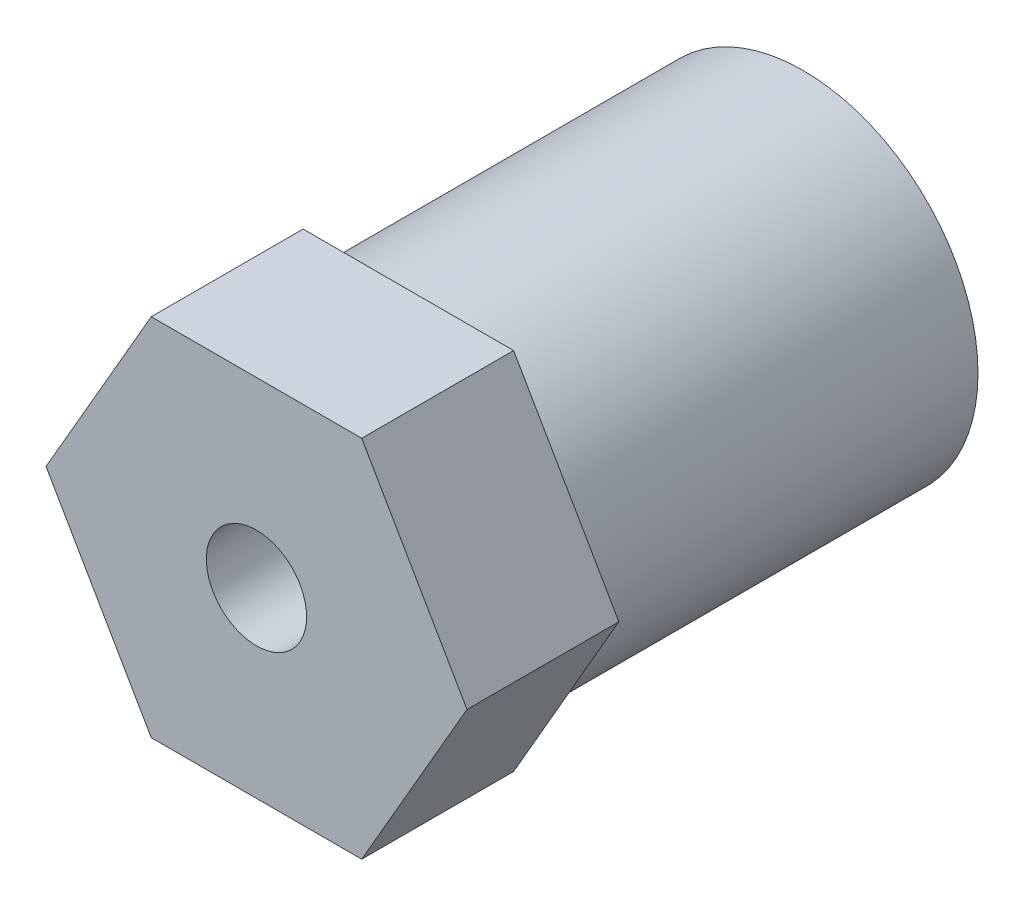
SolidWorks part; units mm, degrees
ref_plane "Front Plane" through (0, 0, 0) normal (0, 0, 1) x (1, 0, 0)
ref_plane "Top Plane" through (0, 0, 0) normal (0, 1, 0) x (1, 0, 0)
ref_plane "Right Plane" through (0, 0, 0) normal (1, 0, 0) x (0, 0, -1)
sketch "Sketch1" plane through (0, 0, 0) normal (1, 0, 0) x (0, 0, -1)
  line L0 (-36.9652, 0) -> (55.5346, 0) construction
  line L1 (0, -2) -> (0, -5.75)
  line L2 (0, -5.75) -> (-13, -5.75)
  line L3 (-13, -5.75) -> (-13, -8.75)
  line L4 (-13, -8.75) -> (-18, -8.75)
  line L5 (-18, -8.75) -> (-18, 0)
  line L7 (0, -2) -> (-13, -2)
  line L8 (-13, -2) -> (-13, 0)
  line L9 (-13, 0) -> (-18, 0)
  point P5 (0, 0)
  dimension "D1" = 18
  dimension "D2" = 5.75
  dimension "D3" = 2
  dimension "D4" = 3
  dimension "D5" = 5
revolve "Revolve1" add sketch "Sketch1" angle 360 about L0
sketch "Sketch4" plane through (0, 0, 18) normal (0, 0, 1) x (1, 0, 0)
  point P0 (0, 0)
hole_wizard "Tap Drill for M4x0.7 Tap1" positions "Sketch7" profile "Sketch8" hole size "M4x0.7" standard "ANSI Metric"
sketch "Sketch7" plane through (0, 0, 18) normal (0, 0, 1) x (1, 0, 0)
  point P0 (0, 0)
sketch "Sketch8" plane through (0, 0, 18) normal (1, 0, 0) x (0, -1, 0)
  line L0 (0, 0) -> (0, 5.9914)
  line L1 (0, 5.9914) -> (1.65, 5)
  line L2 (1.65, 5) -> (1.65, 0)
  line L5 (1.65, 0) -> (0, 0)
  line L10 (0, 5.9914) -> (-1.65, 5) construction
  line L11 (0, -6.35) -> (0, 107.95) construction
  dimension "Hole Dia." = 3.3
  dimension "Hole Depth" = 5
  dimension "Drill Angle" = 118
sketch "Sketch9" plane through (0, 0, 18) normal (0, 0, 1) x (1, 0, 0)
  line L0 (0, 6) -> (0, 0) construction
  line L1 (3.4641, -6) -> (6.9282, 0)
  line L2 (6.9282, 0) -> (3.4641, 6)
  line L3 (3.4641, 6) -> (-3.4641, 6)
  line L4 (-3.4641, 6) -> (-6.9282, 0)
  line L5 (-6.9282, 0) -> (-3.4641, -6)
  line L6 (-3.4641, -6) -> (3.4641, -6)
  circle A0 centre (0, 0) radius 6 construction
  dimension "D1" = 12
extrude "Cut-Extrude1" cut sketch "Sketch9" against normal through all flip side to cut contours L4 L5 L6 L1 L2 L3
